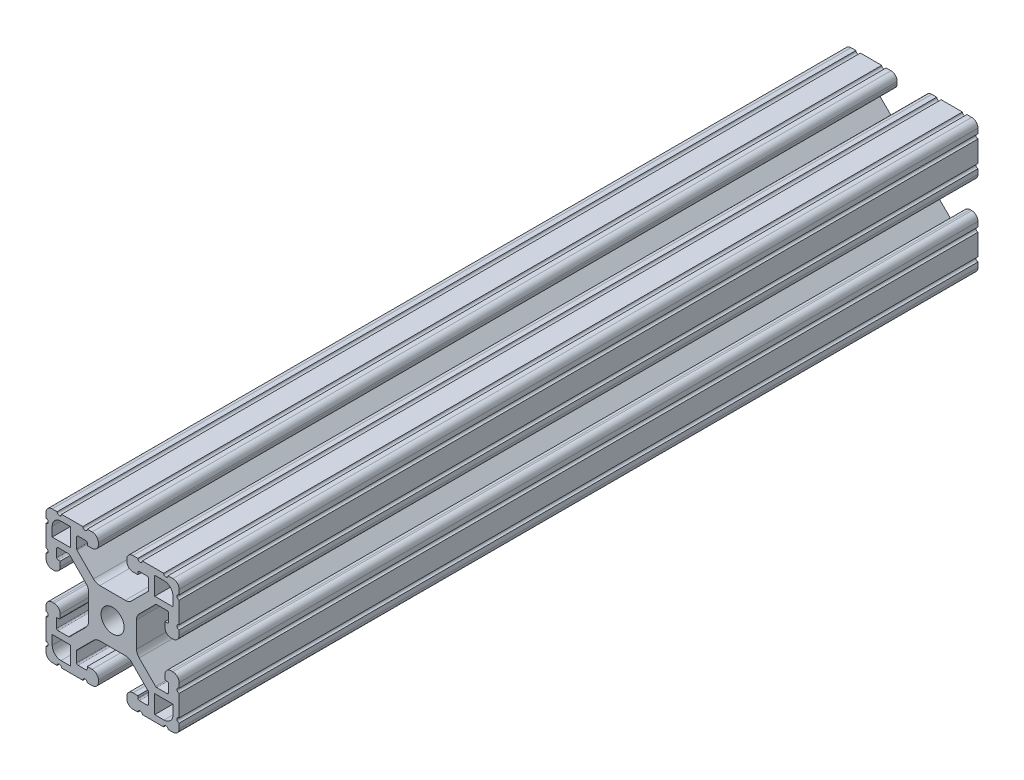
SolidWorks part; units mm, degrees
ref_plane "Front Plane" through (0, 0, 0) normal (0, 0, 1) x (1, 0, 0)
ref_plane "Top Plane" through (0, 0, 0) normal (0, 1, 0) x (1, 0, 0)
ref_plane "Right Plane" through (0, 0, 0) normal (1, 0, 0) x (0, 0, -1)
sketch "Sketch1" plane through (0, 0, 0) normal (0, 0, 1) x (1, 0, 0)
  line L0 (0, -19.05) -> (0, 19.05) construction
  line L1 (19.05, 0) -> (-19.05, 0) construction
  line L2 (4.064, 19.05) -> (-4.064, 19.05) construction
  line L3 (0, -6.858) -> (0, 6.858) construction
  line L4 (-4.064, 19.05) -> (-4.064, 14.986) construction
  line L5 (19.05, -10.287) -> (19.05, 10.287) construction
  line L6 (0, -3.302) -> (0, 3.302) construction
  point P4 (0, 0)
  point P8 (0, 0)
  point P11 (0, 19.05)
  point P14 (0, 0)
  point P18 (19.05, 0)
  point P21 (0, 0)
  dimension "Rail Width" = 38.1
  dimension "Rail Height" = 38.1
  dimension "T-Slot Width" = 8.128
  dimension "Thickness" = 4.064
  dimension "Opening Width" = 20.574
  dimension "Center Hole Diameter" = 6.604
  dimension "Slot Depth" = 12.192
sketch "Sketch2" plane through (0, 0, 0) normal (1, 0, 0) x (0, 0, -1)
  line L0 (-114.3, 0) -> (114.3, 0) construction
  line L1 (0, 19.05) -> (0, -19.05) construction
  line L2 (-25.4, 19.05) -> (25.4, 19.05) construction
  line L4 (3048, -19.05) -> (-3048, -19.05) construction
  point P0 (63.5, 0)
  point P3 (-63.5, 0)
  point P4 (0, 0)
  dimension "D1" = 50.8
  dimension "Rep Length" = 228.6
  dimension "D2" = 50.8
  dimension "Length Range [Min]" = 50.8
  dimension "Length Range [Max]" = 6096
sketch "Sketch3" plane through (0, 0, 0) normal (0, 0, 1) x (1, 0, 0)
  line L1 (19.05, -19.05) -> (-19.05, -19.05)
  line L2 (19.05, -19.05) -> (19.05, 19.05)
  line L3 (19.05, 19.05) -> (-19.05, 19.05)
  line L4 (-19.05, -19.05) -> (-19.05, 19.05)
  line L5 (19.05, -19.05) -> (-19.05, 19.05) construction
  line L6 (19.05, 19.05) -> (-19.05, -19.05) construction
  point P0 (0, 0)
extrude "Boss-Extrude1" add sketch "Sketch3" along normal up to vertex (114.3 mm away) and the other way up to vertex (114.3 mm away) up to point (0, 0, 114.3) other way up to point (0, 0, -114.3)
sketch "Sketch4" plane through (0, 0, 114.3) normal (0, 0, 1) x (1, 0, 0)
  line L4 (4.064, 14.986) -> (4.064, 19.05)
  line L5 (7.239, 14.986) -> (4.064, 14.986)
  line L6 (19.05, 0) -> (-19.05, 0) construction
  line L7 (4.7027, 6.858) -> (-4.7027, 6.858)
  line L8 (-4.7027, 6.858) -> (-10.287, 12.4423)
  line L37 (-19.05, 19.05) -> (-19.05, -19.05) construction
  line L38 (-19.05, -19.05) -> (19.05, -19.05) construction
  line L39 (-10.287, 12.4423) -> (-10.287, 16.002)
  line L40 (-10.287, 16.002) -> (-7.239, 16.002)
  line L41 (-7.239, 16.002) -> (-7.239, 14.986)
  line L42 (-7.239, 14.986) -> (-4.064, 14.986)
  line L43 (-4.064, 14.986) -> (-4.064, 19.05)
  line L44 (-4.064, 19.05) -> (4.064, 19.05)
  line L45 (0, 19.05) -> (0, 0) construction
  line L46 (-19.05, 19.05) -> (0, 0) construction
  line L47 (7.239, 16.002) -> (7.239, 14.986)
  line L48 (10.287, 16.002) -> (7.239, 16.002)
  line L49 (10.287, 12.4423) -> (10.287, 16.002)
  line L50 (4.7027, 6.858) -> (10.287, 12.4423)
  line L51 (-19.05, 0) -> (19.05, 0) construction
  line L52 (4.7027, -6.858) -> (10.287, -12.4423)
  line L53 (10.287, -12.4423) -> (10.287, -16.002)
  line L54 (10.287, -16.002) -> (7.239, -16.002)
  line L55 (7.239, -16.002) -> (7.239, -14.986)
  line L56 (-4.064, -19.05) -> (4.064, -19.05)
  line L57 (-4.064, -14.986) -> (-4.064, -19.05)
  line L58 (-7.239, -14.986) -> (-4.064, -14.986)
  line L59 (-7.239, -16.002) -> (-7.239, -14.986)
  line L60 (-10.287, -16.002) -> (-7.239, -16.002)
  line L61 (-10.287, -12.4423) -> (-10.287, -16.002)
  line L62 (-4.7027, -6.858) -> (-10.287, -12.4423)
  line L63 (4.7027, -6.858) -> (-4.7027, -6.858)
  line L64 (7.239, -14.986) -> (4.064, -14.986)
  line L65 (4.064, -14.986) -> (4.064, -19.05)
  line L66 (-6.858, -4.7027) -> (-12.4423, -10.287)
  line L67 (-12.4423, -10.287) -> (-16.002, -10.287)
  line L68 (-16.002, -10.287) -> (-16.002, -7.239)
  line L69 (-16.002, -7.239) -> (-14.986, -7.239)
  line L70 (-19.05, 4.064) -> (-19.05, -4.064)
  line L71 (-14.986, 4.064) -> (-19.05, 4.064)
  line L72 (-14.986, 7.239) -> (-14.986, 4.064)
  line L73 (-16.002, 7.239) -> (-14.986, 7.239)
  line L74 (-16.002, 10.287) -> (-16.002, 7.239)
  line L75 (-12.4423, 10.287) -> (-16.002, 10.287)
  line L76 (-6.858, 4.7027) -> (-12.4423, 10.287)
  line L77 (-6.858, -4.7027) -> (-6.858, 4.7027)
  line L78 (-14.986, -7.239) -> (-14.986, -4.064)
  line L79 (-14.986, -4.064) -> (-19.05, -4.064)
  line L80 (14.986, -4.064) -> (19.05, -4.064)
  line L81 (14.986, -7.239) -> (14.986, -4.064)
  line L82 (6.858, -4.7027) -> (6.858, 4.7027)
  line L83 (6.858, 4.7027) -> (12.4423, 10.287)
  line L84 (12.4423, 10.287) -> (16.002, 10.287)
  line L85 (16.002, 10.287) -> (16.002, 7.239)
  line L86 (16.002, 7.239) -> (14.986, 7.239)
  line L87 (14.986, 7.239) -> (14.986, 4.064)
  line L88 (14.986, 4.064) -> (19.05, 4.064)
  line L89 (19.05, 4.064) -> (19.05, -4.064)
  line L90 (16.002, -7.239) -> (14.986, -7.239)
  line L91 (16.002, -10.287) -> (16.002, -7.239)
  line L92 (12.4423, -10.287) -> (16.002, -10.287)
  line L93 (6.858, -4.7027) -> (12.4423, -10.287)
  line L94 (19.05, -19.05) -> (19.05, 19.05) construction
  line L95 (12.065, 17.272) -> (17.272, 17.272)
  line L96 (12.065, 17.272) -> (12.065, 12.065)
  line L97 (12.065, 12.065) -> (17.272, 12.065)
  line L98 (17.272, 17.272) -> (17.272, 12.065)
  line L99 (19.05, 19.05) -> (-19.05, 19.05) construction
  line L100 (17.272, -17.272) -> (17.272, -12.065)
  line L101 (12.065, -17.272) -> (17.272, -17.272)
  line L102 (12.065, -17.272) -> (12.065, -12.065)
  line L103 (12.065, -12.065) -> (17.272, -12.065)
  line L104 (-17.272, 17.272) -> (-17.272, 12.065)
  line L105 (-12.065, 12.065) -> (-17.272, 12.065)
  line L106 (-12.065, 17.272) -> (-12.065, 12.065)
  line L107 (-12.065, 17.272) -> (-17.272, 17.272)
  line L108 (-12.065, -12.065) -> (-17.272, -12.065)
  line L109 (-12.065, -17.272) -> (-12.065, -12.065)
  line L110 (-12.065, -17.272) -> (-17.272, -17.272)
  line L111 (-17.272, -17.272) -> (-17.272, -12.065)
  circle A5 centre (0, 0) radius 3.302
  point P21 (0, 6.858)
  point P23 (0, -6.858)
  point P38 (-6.858, 0)
  point P53 (6.858, 0)
  dimension "D1" = 20.574
  dimension "D2" = 3.048
  dimension "D3" = 3.048
  dimension "D4" = 3.048
  dimension "D5" = 1.778
  dimension "D6" = 1.778
  dimension "D7" = 1.778
extrude "Cut-Extrude1" cut sketch "Sketch4" against normal through all
sketch "Sketch5" plane through (0, 0, 114.3) normal (0, 0, 1) x (1, 0, 0)
  line L4 (-4.064, 19.05) -> (-19.05, 19.05) construction
  line L26 (-19.05, 19.05) -> (-19.05, 4.064) construction
  line L27 (-15.875, 19.05) -> (-14.605, 19.05)
  line L28 (-8.509, 19.05) -> (-7.239, 19.05)
  line L29 (-19.05, 15.875) -> (-19.05, 14.605)
  line L30 (-19.05, 8.509) -> (-19.05, 7.239)
  line L31 (8.509, 19.05) -> (7.239, 19.05)
  line L32 (15.875, 19.05) -> (14.605, 19.05)
  line L33 (19.05, 15.875) -> (19.05, 14.605)
  line L34 (19.05, 8.509) -> (19.05, 7.239)
  line L35 (19.05, -8.509) -> (19.05, -7.239)
  line L36 (19.05, -15.875) -> (19.05, -14.605)
  line L37 (15.875, -19.05) -> (14.605, -19.05)
  line L38 (8.509, -19.05) -> (7.239, -19.05)
  line L39 (-8.509, -19.05) -> (-7.239, -19.05)
  line L40 (-15.875, -19.05) -> (-14.605, -19.05)
  line L41 (-19.05, -15.875) -> (-19.05, -14.605)
  line L42 (-19.05, -8.509) -> (-19.05, -7.239)
  line L43 (19.05, 19.05) -> (4.064, 19.05) construction
  line L44 (19.05, 4.064) -> (19.05, 19.05) construction
  line L48 (-14.986, 4.064) -> (-19.05, 4.064) construction
  line L49 (-4.064, 14.986) -> (-4.064, 19.05) construction
  arc A8 (-15.875, 19.05) -> (-14.605, 19.05) centre (-15.24, 19.05) ccw
  arc A9 (-8.509, 19.05) -> (-7.239, 19.05) centre (-7.874, 19.05) ccw
  arc A10 (-19.05, 14.605) -> (-19.05, 15.875) centre (-19.05, 15.24) ccw
  arc A11 (-19.05, 7.239) -> (-19.05, 8.509) centre (-19.05, 7.874) ccw
  arc A12 (7.239, 19.05) -> (8.509, 19.05) centre (7.874, 19.05) ccw
  arc A13 (14.605, 19.05) -> (15.875, 19.05) centre (15.24, 19.05) ccw
  arc A14 (19.05, 15.875) -> (19.05, 14.605) centre (19.05, 15.24) ccw
  arc A15 (19.05, 8.509) -> (19.05, 7.239) centre (19.05, 7.874) ccw
  arc A16 (19.05, -7.239) -> (19.05, -8.509) centre (19.05, -7.874) ccw
  arc A17 (19.05, -14.605) -> (19.05, -15.875) centre (19.05, -15.24) ccw
  arc A18 (15.875, -19.05) -> (14.605, -19.05) centre (15.24, -19.05) ccw
  arc A19 (8.509, -19.05) -> (7.239, -19.05) centre (7.874, -19.05) ccw
  arc A20 (-7.239, -19.05) -> (-8.509, -19.05) centre (-7.874, -19.05) ccw
  arc A21 (-14.605, -19.05) -> (-15.875, -19.05) centre (-15.24, -19.05) ccw
  arc A22 (-19.05, -15.875) -> (-19.05, -14.605) centre (-19.05, -15.24) ccw
  arc A23 (-19.05, -8.509) -> (-19.05, -7.239) centre (-19.05, -7.874) ccw
  dimension "D2" = 0.635
  dimension "D4" = 3.81
  dimension "D5" = 3.81
  dimension "D1" = 3.81
  dimension "D3" = 3.81
  dimension "D7" = 4
extrude "Cut-Extrude2" cut sketch "Sketch5" against normal through all
fillet "Fillet1" radius 2.54 12 edges at (-6.858, 4.7027, 0) (-6.858, -4.7027, 0) (4.7027, -6.858, 0) (-4.7027, -6.858, 0) (6.858, -4.7027, 0) (6.858, 4.7027, 0) (4.7027, 6.858, 0) (-4.7027, 6.858, 0) (-17.272, 17.272, 0) (17.272, 17.272, 0) (17.272, -17.272, 0) (-17.272, -17.272, 0)
fillet "Fillet2" radius 1.778 20 edges at (19.05, -19.05, 0) (19.05, 19.05, 0) (-19.05, -19.05, 0) (-19.05, 19.05, 0) (-14.986, 4.064, 0) (-19.05, 4.064, 0) (-19.05, -4.064, 0) (-14.986, -4.064, 0) (-4.064, -19.05, 0) (-4.064, -14.986, 0) (4.064, -14.986, 0) (4.064, -19.05, 0) (19.05, -4.064, 0) (14.986, -4.064, 0) (19.05, 4.064, 0) (14.986, 4.064, 0) (4.064, 14.986, 0) (4.064, 19.05, 0) (-4.064, 19.05, 0) (-4.064, 14.986, 0)
fillet "Fillet3" radius 0.3969 24 edges at (-14.986, -7.239, 0) (-16.002, -10.287, 0) (-12.4423, -10.287, 0) (-12.4423, 10.287, 0) (-16.002, 7.239, 0) (-16.002, 10.287, 0) (-10.287, 12.4423, 0) (-7.239, 16.002, 0) (-10.287, 16.002, 0) (10.287, 16.002, 0) (7.239, 16.002, 0) (10.287, 12.4423, 0) (16.002, 10.287, 0) (12.4423, 10.287, 0) (16.002, 7.239, 0) (16.002, -7.239, 0) (16.002, -10.287, 0) (12.4423, -10.287, 0) (10.287, -12.4423, 0) (10.287, -16.002, 0) (7.239, -16.002, 0) (-7.239, -16.002, 0) (-10.287, -12.4423, 0) (-10.287, -16.002, 0)
equation "\"D4@Sketch5\"=\"D3@Sketch5\""
equation "\"D5@Sketch5\"=\"D4@Sketch5\""
equation "\"D1@Sketch4\"=\"Opening Width@Sketch1\""
